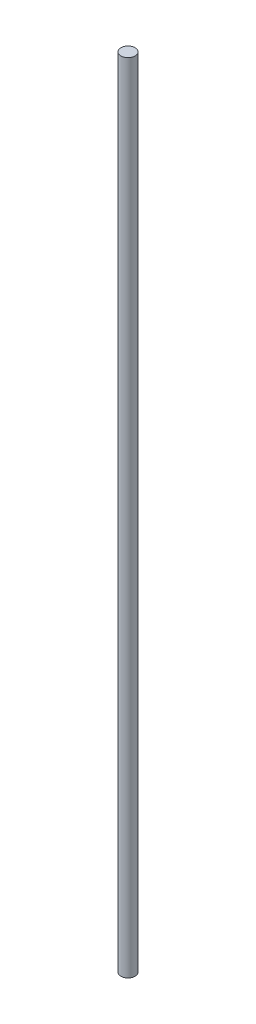
SolidWorks part; units mm, degrees
material "Chrome Stainless Steel"
ref_plane "Front Plane" through (0, 0, 0) normal (0, 0, 1) x (1, 0, 0)
ref_plane "Top Plane" through (0, 0, 0) normal (0, 1, 0) x (1, 0, 0)
ref_plane "Right Plane" through (0, 0, 0) normal (1, 0, 0) x (0, 0, -1)
sketch "Sketch1" plane through (0, 0, 0) normal (0, 1, 0) x (1, 0, 0)
  circle A0 centre (0, 0) radius 3.175
extrude "Boss-Extrude1" add sketch "Sketch1" along normal blind 354.95
